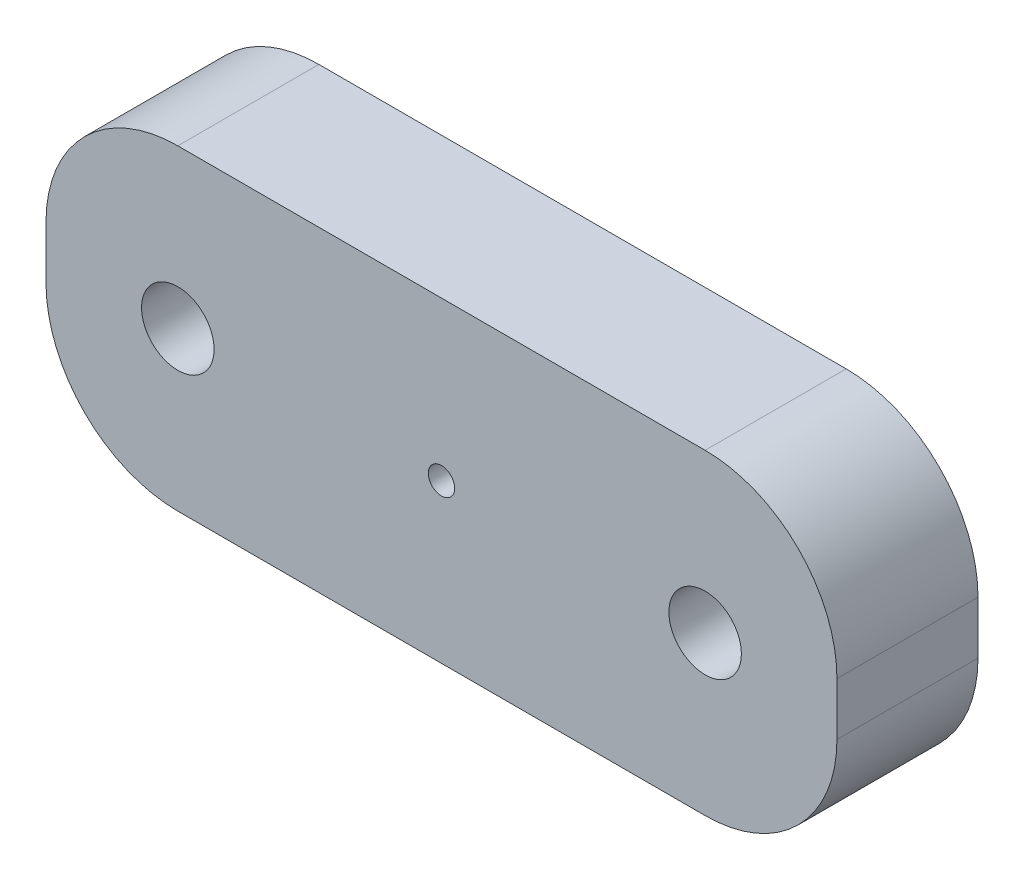
SolidWorks part; units mm, degrees
ref_plane "Front Plane" through (0, 0, 0) normal (0, 0, 1) x (1, 0, 0)
ref_plane "Top Plane" through (0, 0, 0) normal (0, 1, 0) x (1, 0, 0)
ref_plane "Right Plane" through (0, 0, 0) normal (1, 0, 0) x (0, 0, -1)
sketch "Model" plane through (0, 0, 0) normal (0, 0, 1) x (1, 0, 0)
  line L413 (25, 12) -> (5, 12)
  line L414 (30, 5) -> (30, 7)
  line L415 (5, 0) -> (25, 0)
  line L416 (0, 7) -> (0, 5)
  arc A57 (0, 5) -> (5, 0) centre (5, 5) ccw
  arc A58 (5, 12) -> (0, 7) centre (5, 7) ccw
  arc A59 (30, 7) -> (25, 12) centre (25, 7) ccw
  arc A60 (25, 0) -> (30, 5) centre (25, 5) ccw
  circle A61 centre (15, 6) radius 0.5
  circle A62 centre (25, 6) radius 1.375
  circle A63 centre (5, 6) radius 1.375
  circle A64 centre (5, 6) radius 1.2
  circle A65 centre (25, 6) radius 1.2
extrude "Boss-Extrude1" add sketch "Model" along normal blind 5.35 contours L415 A60 L414 A59 L413 A58 L416 A57 A63 A62 A61
